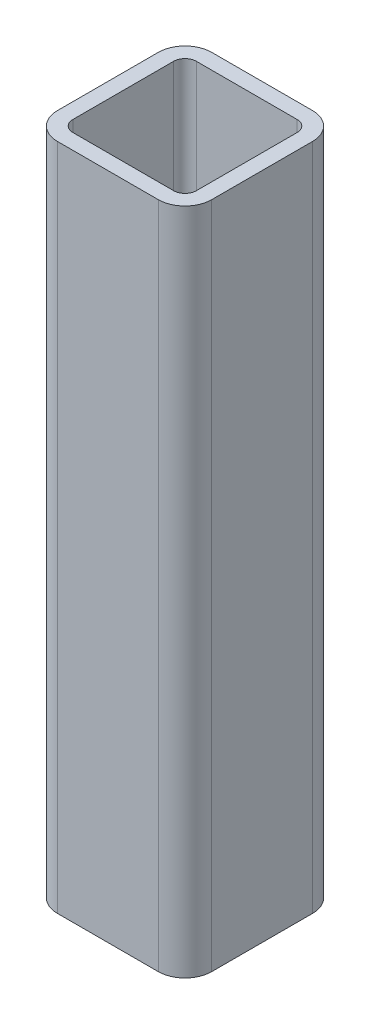
SolidWorks part; units mm, degrees
ref_plane "Front Plane" through (0, 0, 0) normal (0, 0, 1) x (1, 0, 0)
ref_plane "Top Plane" through (0, 0, 0) normal (0, 1, 0) x (1, 0, 0)
ref_plane "Right Plane" through (0, 0, 0) normal (1, 0, 0) x (0, 0, -1)
sketch3d "3DSketch1"
  line L0 (0, 0, 0) -> (0, 130, 0)
  dimension "D1" = 130
other "Square tube 30 X 30 X 2.6(1)"
ref_plane "Plane1" through (0, 0, 0) normal (0, 1, 0) x (1, 0, 0)
sketch "Sketch12" plane through (0, 0, 0) normal (0, 1, 0) x (1, 0, 0)
  line L0 (-9.8, -12) -> (9.8, -12)
  line L1 (-12, -9.8) -> (-12, 9.8)
  line L2 (9.8, 12) -> (-9.8, 12)
  line L3 (12, 9.8) -> (12, -9.8)
  line L4 (-9.8, -15) -> (9.8, -15)
  line L5 (-15, -9.8) -> (-15, 9.8)
  line L6 (9.8, 15) -> (-9.8, 15)
  line L7 (15, 9.8) -> (15, -9.8)
  arc A0 (15, 9.8) -> (9.8, 15) centre (9.8, 9.8) ccw
  arc A1 (9.8, -15) -> (15, -9.8) centre (9.8, -9.8) ccw
  arc A2 (-15, -9.8) -> (-9.8, -15) centre (-9.8, -9.8) ccw
  arc A3 (-9.8, 15) -> (-15, 9.8) centre (-9.8, 9.8) ccw
  arc A4 (-9.8, 12) -> (-12, 9.8) centre (-9.8, 9.8) ccw
  arc A5 (12, 9.8) -> (9.8, 12) centre (9.8, 9.8) ccw
  arc A6 (9.8, -12) -> (12, -9.8) centre (9.8, -9.8) ccw
  arc A7 (-12, -9.8) -> (-9.8, -12) centre (-9.8, -9.8) ccw
  point P0 (-15, 0)
  point P1 (15, 0)
  point P2 (0, 15)
  point P3 (0, -15)
  point P4 (0, 0)
  point P5 (-15, -15)
  point P6 (15, -15)
  point P7 (15, 15)
  point P8 (-15, 15)
  point P33 (0, 0)
  dimension "D1" = 5.2
  dimension "Thickness" = 3
  dimension "V_leg" = 30
